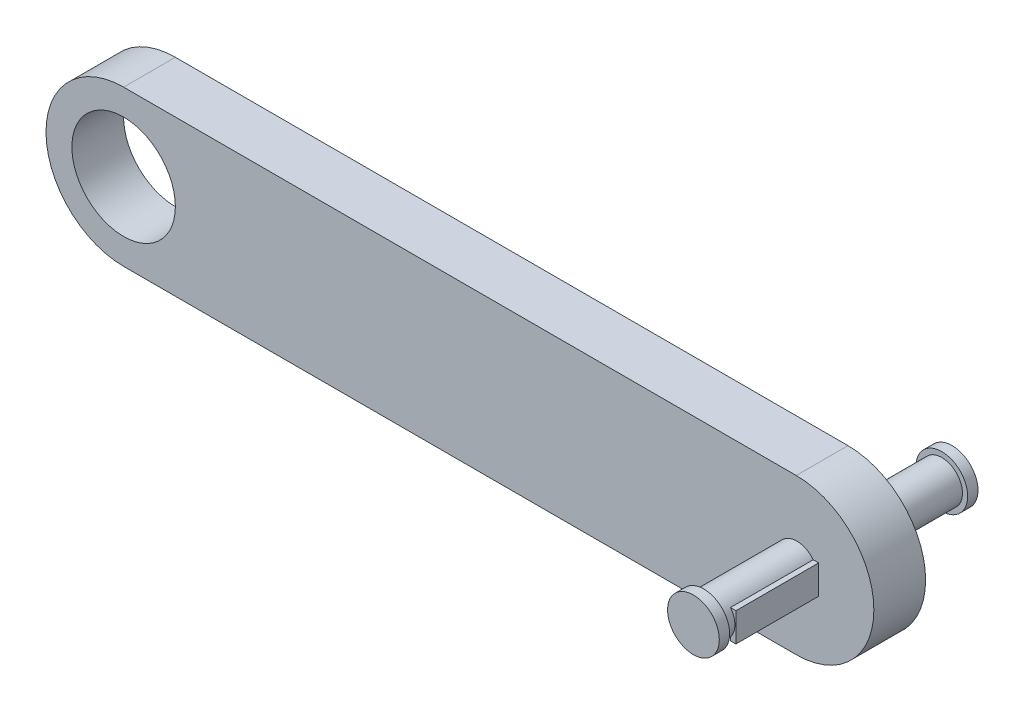
SolidWorks part; units mm, degrees
material "PVC Rigid"
ref_plane "Front Plane" through (0, 0, 0) normal (0, 0, 1) x (1, 0, 0)
ref_plane "Top Plane" through (0, 0, 0) normal (0, 1, 0) x (1, 0, 0)
ref_plane "Right Plane" through (0, 0, 0) normal (1, 0, 0) x (0, 0, -1)
sketch "Sketch1" plane through (0, 0, 0) normal (0, 0, 1) x (1, 0, 0)
  line L1 (-75.8515, 14.0552) -> (6.6985, 14.0552)
  line L3 (-75.8515, -4.9948) -> (6.6985, -4.9948)
  arc A0 (-75.8515, 14.0552) -> (-75.8515, -4.9948) centre (-75.8515, 4.5302) ccw
  arc A1 (6.6985, 14.0552) -> (6.6985, -4.9948) centre (6.6985, 4.5302) cw
  circle A2 centre (-75.8515, 4.5302) radius 6.35
  point P7 (-85.3765, 4.5302)
  point P8 (16.2235, 4.5302)
  dimension "D2" = 101.6
  dimension "D1" = 19.05
extrude "Boss-Extrude1" add sketch "Sketch1" along normal blind 6.35
sketch "Sketch2" plane through (0, 0, 6.35) normal (0, 0, 1) x (1, 0, 0)
  circle A0 centre (6.7794, 4.5752) radius 3.175
  point P2 (38.5534, 2.3246)
  point P3 (23.8106, 0)
extrude "Boss-Extrude2" add sketch "Sketch2" along normal blind 12.7 and the other way blind 19.05
sketch "Sketch9" plane through (0, 0, 19.05) normal (0, 0, 1) x (1, 0, 0)
  circle A0 centre (6.7794, 4.5752) radius 2.5479
extrude "Cut-Extrude1" cut sketch "Sketch9" along direction (0, 0, 1) on the side against the normal up to surface (11.43 mm away) from offset 1.27 flip side to cut offset against normal yes
sketch "Sketch10" plane through (0, 0, -12.7) normal (0, 0, -1) x (-1, 0, 0)
  circle A0 centre (-6.7794, 4.5752) radius 2.5425
extrude "Cut-Extrude2" cut sketch "Sketch10" along direction (0, 0, 1) on the side against the normal up to surface (11.43 mm away) from offset 1.27 flip side to cut offset against normal yes
sketch "Sketch11" plane through (0, 0, 6.35) normal (0, 0, 1) x (1, 0, 0)
  line L1 (8.7876, 6.1434) -> (9.4547, 6.1434)
  line L2 (8.7876, 6.1434) -> (8.7876, 2.6021)
  line L3 (8.7876, 2.6021) -> (9.4547, 2.6021)
  line L4 (9.4547, 6.1434) -> (9.4547, 2.6021)
  circle A0 centre (6.7794, 4.5752) radius 2.5479 construction
  point P6 (9.3978, 2.6021)
  point P7 (9.4547, 6.1434)
extrude "Boss-Extrude3" add sketch "Sketch11" along normal blind 10.16
